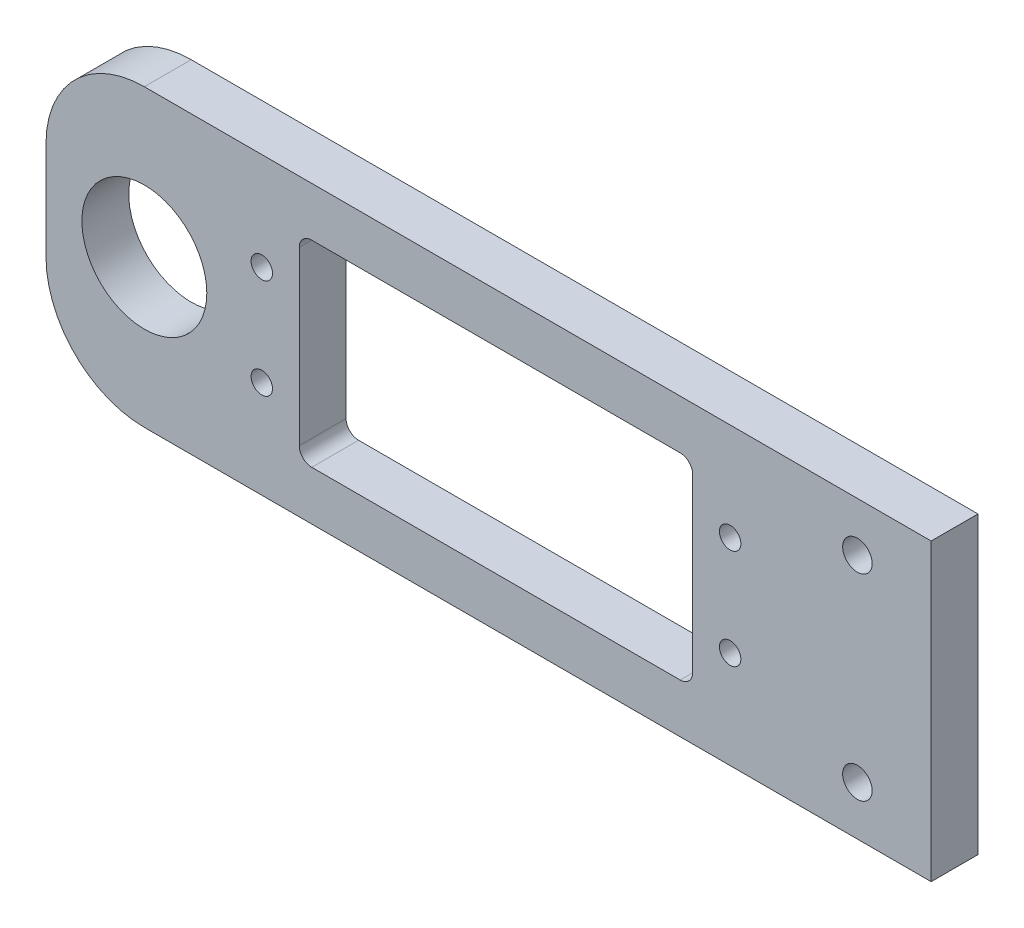
SolidWorks part; units mm, degrees
ref_plane "Front" through (0, 0, 0) normal (0, 0, 1) x (1, 0, 0)
ref_plane "Top" through (0, 0, 0) normal (0, 1, 0) x (1, 0, 0)
ref_plane "Right" through (0, 0, 0) normal (1, 0, 0) x (0, 0, -1)
sketch "Esquisse1" plane through (0, 0, 0) normal (0, 0, 1) x (1, 0, 0)
  line L1 (-45, 15) -> (45, 15)
  line L2 (-45, 15) -> (-45, -15)
  line L3 (-45, -15) -> (45, -15)
  line L4 (45, 15) -> (45, -15)
  line L5 (-45, 15) -> (45, -15) construction
  line L6 (-45, -15) -> (45, 15) construction
  point P0 (0, 0)
  dimension "D1" = 90
  dimension "D2" = 30
extrude "Boss.-Extru.1" add sketch "Esquisse1" along normal blind 4.7625
fillet "Congé1" radius 10 2 edges at (-45, -15, 2.3813) (-45, 15, 2.3813)
sketch "Esquisse2" plane through (0, 0, 4.7625) normal (0, 0, 1) x (1, 0, 0)
  line L0 (-45, 5) -> (-45, -5) construction
  line L1 (45, 15) -> (-35, 15) construction
  circle A0 centre (-35, 0) radius 6.35
  dimension "D1" = 10
  dimension "D2" = 12.7
  dimension "D3" = 15
extrude "Enlèv. mat.-Extru.1" cut sketch "Esquisse2" against normal blind 6
sketch "Esquisse5" plane through (0, 0, 4.7625) normal (0, 0, 1) x (1, 0, 0)
  line L2 (45, 15) -> (-35, 15) construction
  circle A0 centre (-9.6, 0) radius 3.5835 construction
  circle A1 centre (-35, 0) radius 6.35 construction
  dimension "D1" = 25.4
  dimension "D2" = 7.1671
  dimension "D3" = 15
sketch "Esquisse3" plane through (0, 0, 4.7625) normal (0, 0, 1) x (1, 0, 0)
  line L0 (45, 15) -> (-35, 15) construction
  line L1 (-19.25, 10) -> (20.75, 10)
  line L2 (-19.25, 10) -> (-19.25, -10)
  line L3 (-19.25, -10) -> (20.75, -10)
  line L4 (20.75, 10) -> (20.75, -10)
  circle A0 centre (-9.6, 0) radius 3.5835 construction
  dimension "D1" = 20
  dimension "D2" = 5
  dimension "D3" = 40
  dimension "D4" = 9.65
extrude "Enlèv. mat.-Extru.2" cut sketch "Esquisse3" against normal up to next
fillet "Congé2" radius 1.27 4 edges at (20.75, -10, 2.3813) (-19.25, -10, 2.3813) (20.75, 10, 2.3813) (-19.25, 10, 2.3813)
sketch "Esquisse4" plane through (0, 0, 4.7625) normal (0, 0, 1) x (1, 0, 0)
  line L0 (-19.25, 8.73) -> (-19.25, -8.73) construction
  line L1 (19.48, 10) -> (-17.98, 10) construction
  line L2 (50, 0) -> (-50, 0) construction
  line L4 (0.75, 10) -> (0.75, -10) construction
  line L5 (-17.98, -10) -> (19.48, -10) construction
  circle A0 centre (-23.06, 5.08) radius 1.09
  circle A1 centre (-23.06, -5.08) radius 1.09
  circle A2 centre (24.56, -5.08) radius 1.09
  circle A3 centre (24.56, 5.08) radius 1.09
  dimension "D3" = 2.18
  dimension "D1" = 3.81
  dimension "D2" = 4.92
extrude "Enlèv. mat.-Extru.3" cut sketch "Esquisse4" against normal up to next
sketch "Esquisse6" plane through (0, 0, 4.7625) normal (0, 0, 1) x (1, 0, 0)
  line L0 (45, -15) -> (45, 15) construction
  line L1 (45, 15) -> (-35, 15) construction
  line L2 (50, 0) -> (-50, 0) construction
  circle A0 centre (37.5, 10) radius 1.5
  circle A1 centre (37.5, -10) radius 1.5
  dimension "D1" = 3
  dimension "D2" = 7.5
  dimension "D3" = 5
extrude "Enlèv. mat.-Extru.4" cut sketch "Esquisse6" against normal up to next
